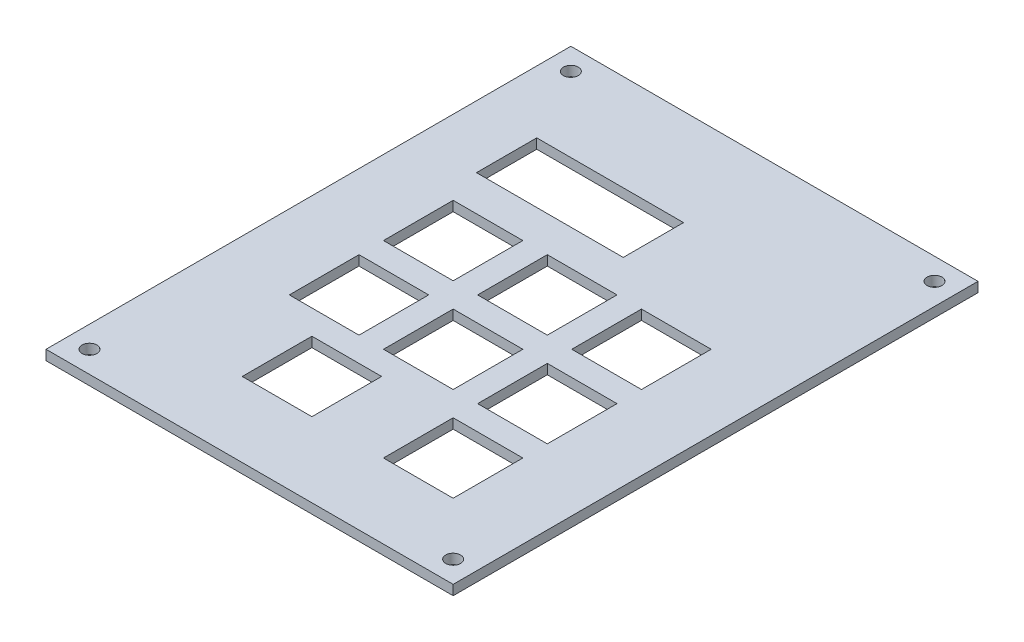
SolidWorks part; units mm, degrees
ref_plane "Front Plane" through (0, 0, 0) normal (0, 0, 1) x (1, 0, 0)
ref_plane "Top Plane" through (0, 0, 0) normal (0, 1, 0) x (1, 0, 0)
ref_plane "Right Plane" through (0, 0, 0) normal (1, 0, 0) x (0, 0, -1)
sketch "Sketch1" plane through (0, 0, 0) normal (0, 1, 0) x (1, 0, 0)
  line L1 (0, 0) -> (82.375, 0)
  line L2 (0, 0) -> (0, 106.187)
  line L3 (0, 106.187) -> (82.375, 106.187)
  line L4 (82.375, 0) -> (82.375, 106.187)
  dimension "D1" = 106.187
  dimension "D2" = 82.375
extrude "Acrylic-Sheet" add sketch "Sketch1" along normal blind 2
sketch "Sketch2" plane through (0, 2, 0) normal (0, 1, 0) x (1, 0, 0)
  line L0 (15.0875, 67.2875) -> (29.1875, 67.2875)
  line L1 (12.6, 86.687) -> (42.3, 86.687)
  line L2 (0, 101.787) -> (82.375, 101.787) construction
  line L3 (0, 106.187) -> (0, 0) construction
  line L4 (82.375, 0) -> (82.375, 106.187) construction
  line L5 (77.975, 106.187) -> (77.975, 0) construction
  line L6 (82.375, 106.187) -> (0, 106.187) construction
  line L7 (0, 0) -> (82.375, 0) construction
  line L8 (0, 4.4) -> (82.375, 4.4) construction
  line L9 (4.4, 106.187) -> (4.4, 0) construction
  line L10 (12.6, 86.687) -> (12.6, 74.487)
  line L11 (12.6, 74.487) -> (42.3, 74.487)
  line L12 (42.3, 86.687) -> (42.3, 74.487)
  line L45 (15.0875, 67.2875) -> (15.0875, 53.1875)
  line L46 (15.0875, 53.1875) -> (29.1875, 53.1875)
  line L47 (29.1875, 67.2875) -> (29.1875, 53.1875)
  line L48 (34.1375, 67.2875) -> (48.2375, 67.2875)
  line L49 (34.1375, 67.2875) -> (34.1375, 53.1875)
  line L50 (34.1375, 53.1875) -> (48.2375, 53.1875)
  line L51 (48.2375, 67.2875) -> (48.2375, 53.1875)
  line L52 (53.1875, 67.2875) -> (67.2875, 67.2875)
  line L53 (53.1875, 67.2875) -> (53.1875, 53.1875)
  line L54 (53.1875, 53.1875) -> (67.2875, 53.1875)
  line L55 (67.2875, 67.2875) -> (67.2875, 53.1875)
  line L56 (15.0875, 48.2375) -> (29.1875, 48.2375)
  line L57 (15.0875, 48.2375) -> (15.0875, 34.1375)
  line L58 (15.0875, 34.1375) -> (29.1875, 34.1375)
  line L59 (29.1875, 48.2375) -> (29.1875, 34.1375)
  line L60 (34.1375, 48.2375) -> (48.2375, 48.2375)
  line L61 (34.1375, 48.2375) -> (34.1375, 34.1375)
  line L62 (34.1375, 34.1375) -> (48.2375, 34.1375)
  line L63 (48.2375, 48.2375) -> (48.2375, 34.1375)
  line L64 (53.1875, 48.2375) -> (67.2875, 48.2375)
  line L65 (53.1875, 48.2375) -> (53.1875, 34.1375)
  line L66 (53.1875, 34.1375) -> (67.2875, 34.1375)
  line L67 (67.2875, 48.2375) -> (67.2875, 34.1375)
  line L68 (24.6125, 29.1875) -> (38.7125, 29.1875)
  line L69 (24.6125, 29.1875) -> (24.6125, 15.0875)
  line L70 (24.6125, 15.0875) -> (38.7125, 15.0875)
  line L71 (38.7125, 29.1875) -> (38.7125, 15.0875)
  line L72 (22.1375, 106.187) -> (22.1375, 0) construction
  line L73 (41.1875, 106.187) -> (41.1875, 0) construction
  line L78 (60.2375, 106.187) -> (60.2375, 0) construction
  line L79 (0, 60.2375) -> (82.375, 60.2375) construction
  line L80 (0, 41.1875) -> (82.375, 41.1875) construction
  line L81 (0, 22.1375) -> (82.375, 22.1375) construction
  line L82 (53.1875, 29.1875) -> (67.2875, 29.1875)
  line L83 (53.1875, 29.1875) -> (53.1875, 15.0875)
  line L84 (53.1875, 15.0875) -> (67.2875, 15.0875)
  line L85 (67.2875, 29.1875) -> (67.2875, 15.0875)
  line L86 (31.6625, 106.187) -> (31.6625, 0) construction
  line L87 (4.4, 13.7932) -> (22.1375, 13.7932) construction
  line L88 (13.1145, 22.1375) -> (13.1145, 4.4) construction
  circle A0 centre (4.4, 101.787) radius 1.5
  circle A1 centre (77.975, 101.787) radius 1.5
  circle A2 centre (77.975, 4.4) radius 1.5
  circle A3 centre (4.4, 4.4) radius 1.5
  point P72 (22.1375, 53.1875)
  point P73 (15.0875, 60.2375)
  point P74 (34.1375, 60.2375)
  point P75 (41.1875, 53.1875)
  point P76 (53.1875, 60.2375)
  point P77 (60.2375, 53.1875)
  point P78 (15.0875, 41.1875)
  point P79 (22.1375, 34.1375)
  point P80 (48.2375, 41.1875)
  point P81 (41.1875, 34.1375)
  point P82 (60.2375, 34.1375)
  point P83 (53.1875, 41.1875)
  point P84 (24.6125, 22.1375)
  point P85 (53.1875, 22.1375)
  point P86 (60.2375, 15.0875)
  point P89 (31.6625, 15.0875)
  dimension "D1" = 3
  dimension "D2" = 4.4
  dimension "D3" = 4.4
  dimension "D4" = 4.4
  dimension "D5" = 4.4
  dimension "D6" = 14.1
  dimension "D7" = 14.1
  dimension "D8" = 14.1
  dimension "D9" = 14.1
  dimension "D10" = 14.1
  dimension "D11" = 14.1
  dimension "D12" = 14.1
  dimension "D13" = 14.1
  dimension "D14" = 19.05
  dimension "D15" = 19.05
  dimension "D16" = 19.05
  dimension "D17" = 19.05
  dimension "D18" = 9.525
  dimension "D19" = 29.7
  dimension "D20" = 12.2
  dimension "D21" = 19.5
  dimension "D22" = 12.6
extrude "Acrylic-Cut" cut sketch "Sketch2" against normal through all
